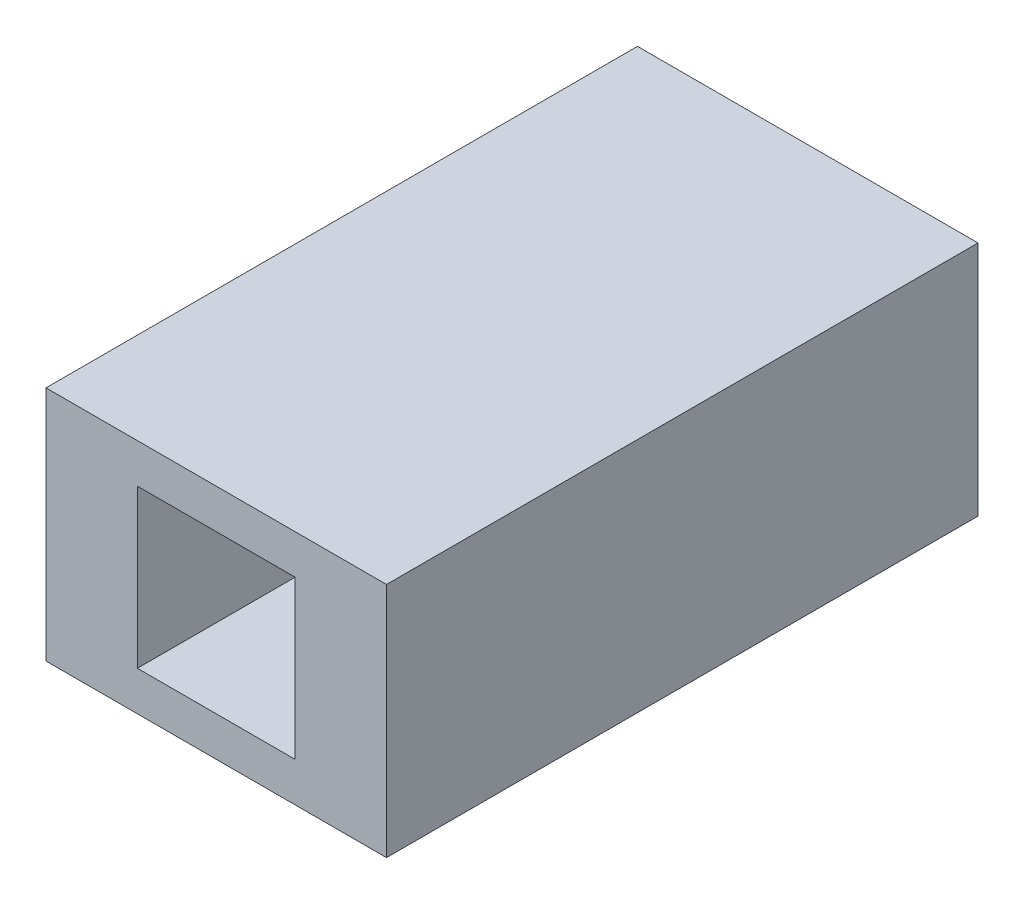
SolidWorks part; units mm, degrees
ref_plane "Front Plane" through (0, 0, 0) normal (0, 0, 1) x (1, 0, 0)
ref_plane "Top Plane" through (0, 0, 0) normal (0, 1, 0) x (1, 0, 0)
ref_plane "Right Plane" through (0, 0, 0) normal (1, 0, 0) x (0, 0, -1)
sketch "Sketch1" plane through (0, 0, 0) normal (0, 0, 1) x (1, 0, 0)
  line L0 (43.175, -50) -> (43.175, 30) construction
  line L1 (-43.175, -30) -> (43.175, -30)
  line L2 (-43.175, -30) -> (-43.175, 30)
  line L3 (-43.175, 30) -> (43.175, 30)
  line L4 (43.175, -30) -> (43.175, 30)
  line L5 (-43.175, -30) -> (43.175, 30) construction
  line L6 (-43.175, 30) -> (43.175, -30) construction
  line L7 (-43.175, -50) -> (-43.175, 30) construction
  line L8 (43.175, -50) -> (43.175, 30) construction
  line L9 (-43.175, -50) -> (-43.175, 30) construction
  point P0 (0, 0)
  dimension "D1" = 86.35
  dimension "D2" = 86.35
  dimension "D3" = 60
extrude "Boss-Extrude1" add sketch "Sketch1" along normal blind 150
sketch "Sketch2" plane through (0, 0, 150) normal (0, 0, -1) x (-1, 0, 0)
  line L1 (-20, -20) -> (20, -20)
  line L2 (-20, -20) -> (-20, 20)
  line L3 (-20, 20) -> (20, 20)
  line L4 (20, -20) -> (20, 20)
  line L5 (-20, -20) -> (20, 20) construction
  line L6 (-20, 20) -> (20, -20) construction
  point P0 (0, 0)
  dimension "D1" = 40
  dimension "D2" = 40
extrude "Cut-Extrude1" cut sketch "Sketch2" along normal blind 145
equation "\"D2@Sketch1\"=\"D1@Sketch1\""
